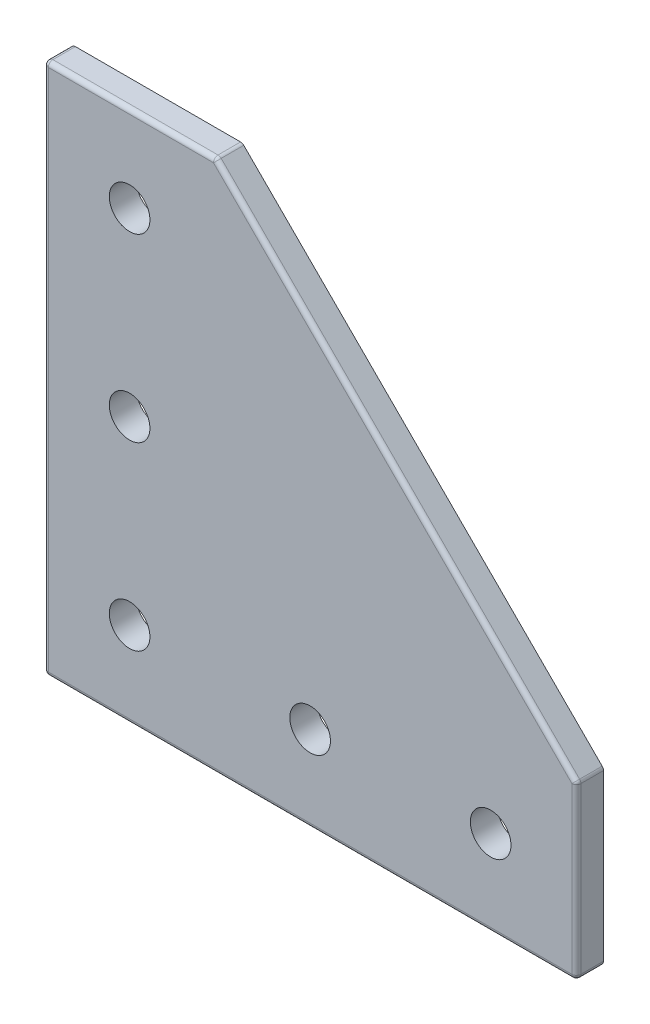
SolidWorks part; units mm, degrees
ref_plane "Front Plane" through (0, 0, 0) normal (0, 0, 1) x (1, 0, 0)
ref_plane "Top Plane" through (0, 0, 0) normal (0, 1, 0) x (1, 0, 0)
ref_plane "Right Plane" through (0, 0, 0) normal (1, 0, 0) x (0, 0, -1)
sketch "Sketch1" plane through (0, 0, 0) normal (0, 0, 1) x (1, 0, 0)
  line L0 (0, 0) -> (0, 118)
  line L1 (19, 19) -> (59, 19) construction
  line L2 (59, 19) -> (99, 19) construction
  line L3 (19, 19) -> (19, 59) construction
  line L4 (38, 118) -> (0, 118)
  line L5 (118, 0) -> (0, 0)
  line L6 (19, 59) -> (19, 99) construction
  line L7 (118, 38) -> (118, 0)
  line L8 (38, 118) -> (118, 38)
  line L9 (118, 19) -> (99, 19) construction
  line L10 (19, 118) -> (19, 99) construction
  circle A0 centre (19, 19) radius 4.5
  circle A1 centre (59, 19) radius 4.5
  circle A2 centre (99, 19) radius 4.5
  circle A3 centre (19, 59) radius 4.5
  circle A4 centre (19, 99) radius 4.5
  dimension "D1" = 40
  dimension "E" = 9
  dimension "D2" = 19
  dimension "C" = 118
  dimension "D3" = 40
  dimension "B" = 118
  dimension "D4" = 19
extrude "Boss-Extrude1" add sketch "Sketch1" along normal mid plane 6
fillet "Fillet1" radius 1 10 edges at (0, 0, 0) (0, 59, 3) (59, 0, 3) (118, 19, 3) (118, 0, 0) (19, 118, 3) (0, 118, 0) (78, 78, 3) (118, 38, 0) (38, 118, 0)
